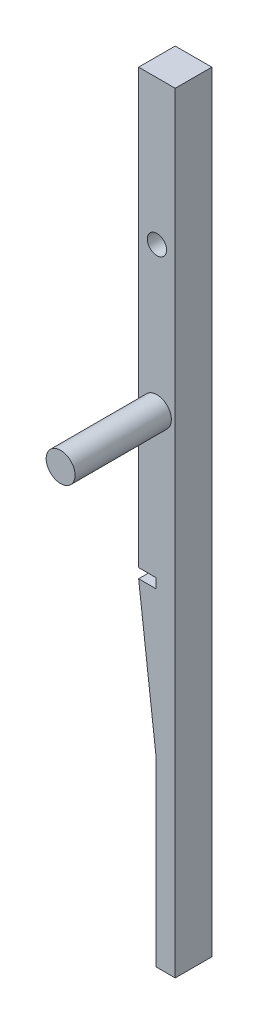
SolidWorks part; units mm, degrees
ref_plane "Plano frontal" through (0, 0, 0) normal (0, 0, 1) x (1, 0, 0)
ref_plane "Plano superior" through (0, 0, 0) normal (0, 1, 0) x (1, 0, 0)
ref_plane "Plano direito" through (0, 0, 0) normal (1, 0, 0) x (0, 0, -1)
sketch "Esboço1" plane through (0, 0, 0) normal (0, 0, 1) x (1, 0, 0)
  line L0 (-16.5244, 27.625) -> (-16.5244, -17.375)
  line L1 (-16.5244, -17.375) -> (-12.7244, -17.375)
  line L2 (-12.7244, -17.375) -> (-12.7244, 27.625)
  line L3 (-12.7244, 27.625) -> (-16.5244, 27.625)
  dimension "D1" = 45
  dimension "D2" = 3.8
extrude "Ressalto-extrusão1" add sketch "Esboço1" along normal blind 3.8
sketch "Esboço2" plane through (0, 0, 3.8) normal (0, 0, 1) x (1, 0, 0)
  line L0 (-12.7244, -17.375) -> (-12.7244, 27.625) construction
  line L1 (-12.7244, 27.625) -> (-16.5244, 27.625) construction
  circle A0 centre (-14.6244, -2.375) radius 1.5
  dimension "D3" = 3
  dimension "D1" = 1.9
  dimension "D2" = 30
extrude "Ressalto-extrusão2" add sketch "Esboço2" along normal blind 10
sketch "Esboço3" plane through (0, -17.375, 0) normal (0, -1, 0) x (-1, 0, 0)
  line L0 (14.7244, 0) -> (14.7244, -3.8)
  line L1 (16.5244, 0) -> (12.7244, 0) construction
  line L2 (16.5244, -3.8) -> (12.7244, -3.8) construction
  line L3 (14.7244, -3.8) -> (12.7244, -3.8)
  line L4 (12.7244, -3.8) -> (12.7244, 0)
  line L5 (12.7244, 0) -> (14.7244, 0)
  dimension "D1" = 2
extrude "Ressalto-extrusão3" add sketch "Esboço3" along normal blind 1
sketch "Esboço5" plane through (0, 0, 3.8) normal (0, 0, 1) x (1, 0, 0)
  line L0 (-12.7244, -18.375) -> (-12.7244, 27.625) construction
  line L1 (-12.7244, 27.625) -> (-16.5244, 27.625) construction
  circle A0 centre (-14.6244, 12.625) radius 1
  dimension "D2" = 2
  dimension "D1" = 1.9
  dimension "D3" = 15
extrude "Corte-extrusão1" cut sketch "Esboço5" against normal blind 4
sketch "Esboço9" plane through (0, 0, 3.8) normal (0, 0, 1) x (1, 0, 0)
  line L0 (-12.7244, -18.375) -> (-12.7244, -33.375)
  line L1 (-12.7244, -33.375) -> (-14.7244, -33.375)
  line L2 (-16.5244, -18.375) -> (-12.7244, -18.375)
  line L3 (-14.7244, -33.375) -> (-16.5244, -18.375)
  dimension "D1" = 3.8
  dimension "D2" = 2
  dimension "D3" = 15
extrude "Ressalto-extrusão7" add sketch "Esboço9" against normal blind 3.8
sketch "Esboço10" plane through (0, -33.375, 0) normal (0, -1, 0) x (-1, 0, 0)
  line L0 (12.7244, -3.8) -> (14.7244, -3.8)
  line L1 (14.7244, -3.8) -> (14.7244, 0)
  line L2 (14.7244, 0) -> (14.7244, -3.8) construction
  line L3 (14.7244, 0) -> (12.7244, 0)
  line L4 (12.7244, 0) -> (12.7244, -3.8)
extrude "Ressalto-extrusão8" add sketch "Esboço10" along normal blind 19
